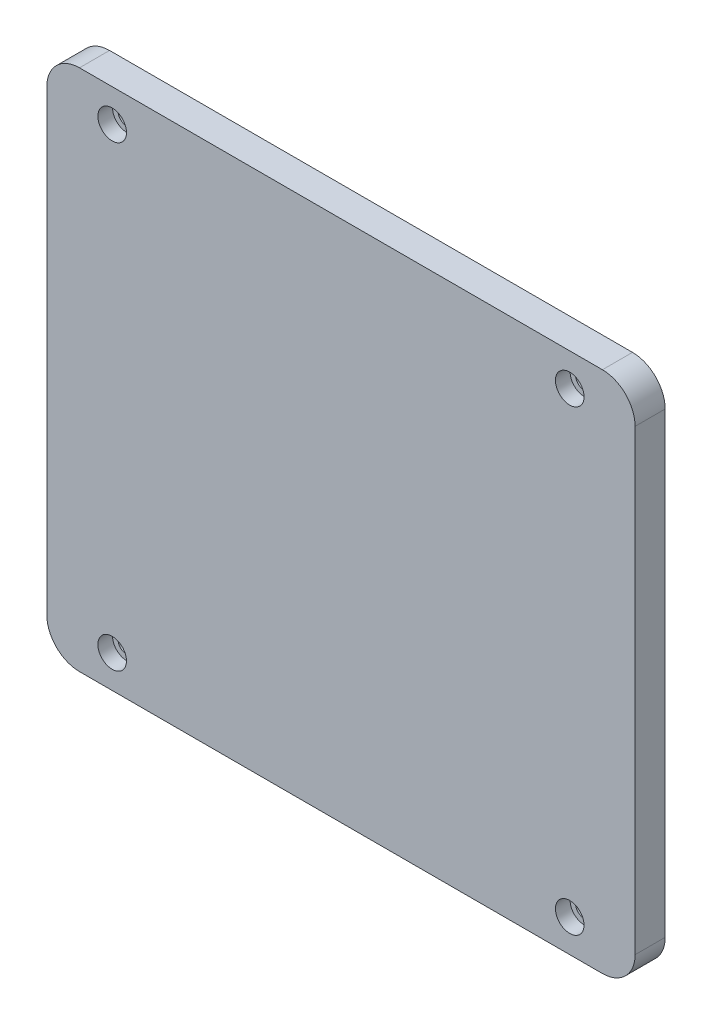
SolidWorks part; units mm, degrees
material "6061-T6 (SS)"
ref_plane "Front Plane" through (0, 0, 0) normal (0, 0, 1) x (1, 0, 0)
ref_plane "Top Plane" through (0, 0, 0) normal (0, 1, 0) x (1, 0, 0)
ref_plane "Right Plane" through (0, 0, 0) normal (1, 0, 0) x (0, 0, -1)
sketch "Sketch1" plane through (0, 0, 0) normal (0, 0, 1) x (1, 0, 0)
  line L13 (-57.15, -50.8) -> (57.15, -50.8)
  line L14 (-57.15, -50.8) -> (-57.15, 50.8)
  line L15 (-57.15, 50.8) -> (57.15, 50.8)
  line L16 (57.15, -50.8) -> (57.15, 50.8)
  line L17 (-57.15, -50.8) -> (57.15, 50.8) construction
  line L18 (-57.15, 50.8) -> (57.15, -50.8) construction
  point P0 (0, 0)
  dimension "D1" = 114.3
  dimension "D2" = 101.6
extrude "Boss-Extrude1" add sketch "Sketch1" along normal blind 5.842
hole_wizard "CBORE for #4 Socket Head Cap Screw1" positions "Sketch2" profile "Sketch3" counterbore size "#4" standard "ANSI Inch" end condition through all
sketch "Sketch2" plane through (0, 0, 5.842) normal (0, 0, 1) x (1, 0, 0)
  line L0 (44.45, 44.45) -> (-44.45, 44.45) construction
  line L1 (-44.45, 44.45) -> (-44.45, -44.45) construction
  line L2 (-44.45, -44.45) -> (44.45, -44.45) construction
  line L3 (44.45, -44.45) -> (44.45, 44.45) construction
  line L4 (44.45, 0) -> (-44.45, 0) construction
  circle A2 centre (0, 0) radius 62.8618
  point P0 (-44.45, 44.45)
  point P2 (-44.45, -44.45)
  point P4 (44.45, -44.45)
  point P6 (44.45, 44.45)
  point P25 (0, 0)
  dimension "D1" = 88.9
sketch "Sketch3" plane through (-44.45, 44.45, 5.842) normal (1, 0, 0) x (0, -1, 0)
  line L0 (0, 0) -> (0, 5.842)
  line L1 (0, 5.842) -> (1.7272, 5.842)
  line L3 (1.7272, 5.842) -> (1.7272, 2.8448)
  line L4 (1.7272, 2.8448) -> (2.7788, 2.8448)
  line L5 (2.7788, 2.8448) -> (2.7788, 0)
  line L7 (2.7788, 0) -> (0, 0)
  line L11 (0, -6.35) -> (0, 107.95) construction
  dimension "Thru Hole Dia." = 3.4544
  dimension "Thru Hole Depth" = 5.842
  dimension "C'Bore Dia." = 5.5575
  dimension "C'Bore Depth" = 2.8448
fillet "Fillet1" radius 6.35 4 edges at (-57.15, 50.8, 2.921) (57.15, 50.8, 2.921) (57.15, -50.8, 2.921) (-57.15, -50.8, 2.921)
sketch "Sketch4" plane through (0, 0, 5.842) normal (0, 0, 1) x (1, 0, 0)
  text T0 "SUBT" font "Century Gothic" height 25.4
